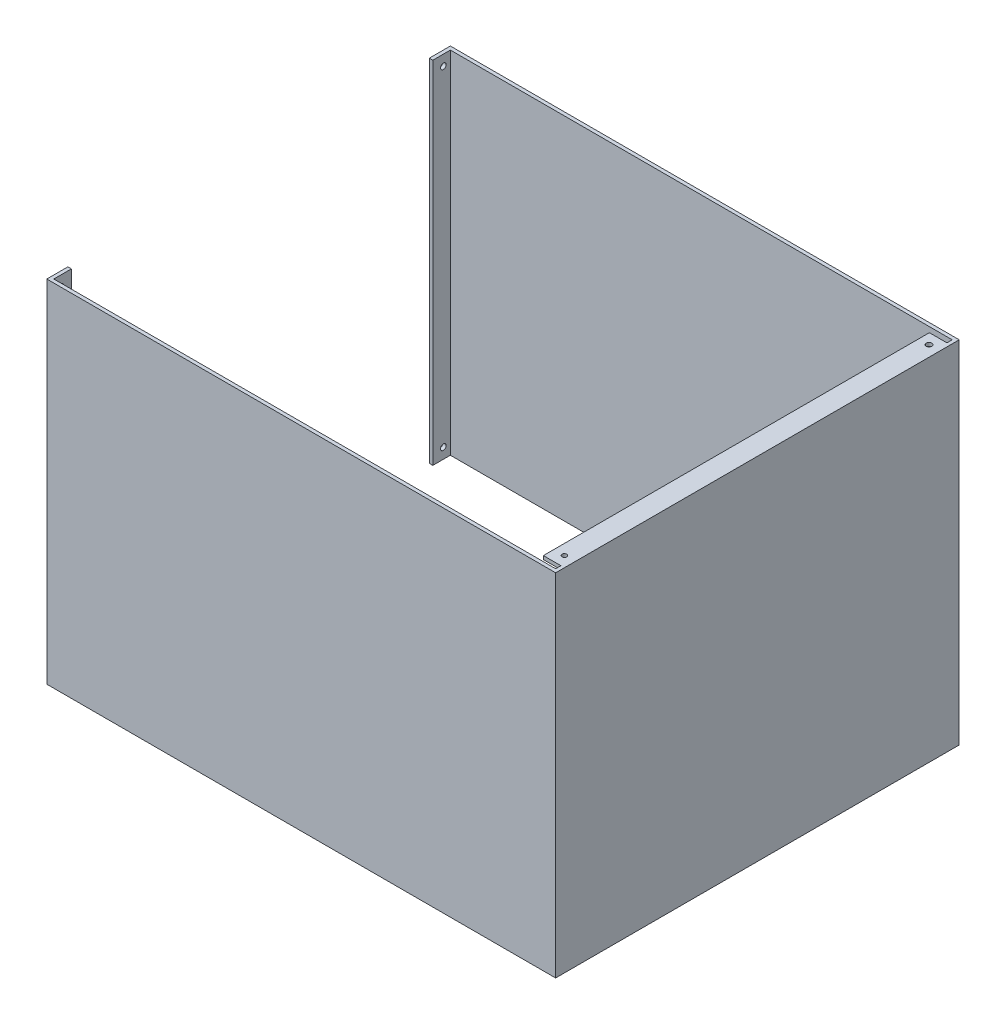
SolidWorks part; units mm, degrees
ref_plane "前视基准面" through (0, 0, 0) normal (0, 0, 1) x (1, 0, 0)
ref_plane "上视基准面" through (0, 0, 0) normal (0, 1, 0) x (1, 0, 0)
ref_plane "右视基准面" through (0, 0, 0) normal (1, 0, 0) x (0, 0, -1)
sketch "草图1" plane through (0, 0, 0) normal (0, 1, 0) x (1, 0, 0)
  line L1 (-145, 115) -> (145, 115)
  line L2 (-145, 115) -> (-145, -115)
  line L3 (-145, -115) -> (145, -115)
  line L4 (145, 115) -> (145, -115)
  line L5 (-145, 115) -> (145, -115) construction
  line L6 (-145, -115) -> (145, 115) construction
  point P0 (0, 0)
  dimension "D1" = 290
  dimension "D2" = 230
extrude "凸台-拉伸1" add sketch "草图1" along normal blind 200
sketch "草图2" plane through (0, 200, 0) normal (0, 1, 0) x (1, 0, 0)
  line L1 (-143, 113) -> (143, 113)
  line L2 (-143, 113) -> (-143, -113)
  line L3 (-143, -113) -> (143, -113)
  line L4 (143, 113) -> (143, -113)
  line L5 (-143, 113) -> (143, -113) construction
  line L6 (-143, -113) -> (143, 113) construction
  point P0 (0, 0)
  dimension "D1" = 286
  dimension "D2" = 226
extrude "切除-拉伸1" cut sketch "草图2" against normal blind 200
sketch "草图3" plane through (-145, 0, 0) normal (-1, 0, 0) x (0, 0, 1)
  line L0 (-115, 200) -> (115, 200) construction
  line L1 (-113, 200) -> (113, 200)
  line L2 (-113, 200) -> (-113, 0)
  line L3 (-113, 0) -> (113, 0)
  line L4 (113, 200) -> (113, 0)
  line L5 (-115, 0) -> (115, 0) construction
  line L6 (115, 200) -> (115, 0) construction
  line L7 (-115, 200) -> (-115, 0) construction
  dimension "D1" = 2
  dimension "D2" = 2
extrude "切除-拉伸2" cut sketch "草图3" against normal blind 2 contours L4 L3 L2 L1
sketch "草图5" plane through (0, 200, 0) normal (0, 1, 0) x (1, 0, 0)
  line L0 (143, -113) -> (143, 113) construction
  line L1 (143, 110) -> (133, 110)
  line L2 (143, 110) -> (143, -110)
  line L3 (143, -110) -> (133, -110)
  line L4 (133, 110) -> (133, -110)
  line L5 (143, 113) -> (-145, 113) construction
  dimension "D1" = 10
  dimension "D2" = 220
  dimension "D3" = 3
extrude "凸台-拉伸2" add sketch "草图5" against normal blind 2
sketch "草图6" plane through (0, 200, 0) normal (0, 1, 0) x (1, 0, 0)
  line L0 (145, -115) -> (145, 115) construction
  line L1 (143, 110) -> (133, 110) construction
  circle A0 centre (138.8254, 104) radius 1.6
  dimension "D1" = 3.2
  dimension "D2" = 6.1746
  dimension "D3" = 6
extrude "切除-拉伸3" cut sketch "草图6" against normal blind 2
sketch "草图7" plane through (0, 200, 0) normal (0, 1, 0) x (1, 0, 0)
  line L0 (145, -115) -> (145, 115) construction
  line L1 (133, -110) -> (143, -110) construction
  circle A0 centre (139, -104) radius 1.3505
  dimension "D1" = 2.7011
  dimension "D2" = 6
  dimension "D3" = 6
extrude "切除-拉伸4" cut sketch "草图7" against normal blind 2
sketch "草图8" plane through (-145, 0, 0) normal (-1, 0, 0) x (0, 0, 1)
  line L0 (113, 0) -> (113, 200) construction
  line L1 (113, 200) -> (103, 200)
  line L2 (113, 200) -> (113, 0)
  line L3 (113, 0) -> (103, 0)
  line L4 (103, 200) -> (103, 0)
  line L5 (113, 200) -> (110, 200) construction
  dimension "D1" = 10
  dimension "D2" = 200
  dimension "D3" = 0
extrude "凸台-拉伸3" add sketch "草图8" against normal blind 2
sketch "草图9" plane through (-145, 0, 0) normal (-1, 0, 0) x (0, 0, 1)
  line L0 (115, 200) -> (115, 0) construction
  line L1 (103, 200) -> (115, 200) construction
  circle A0 centre (109, 194) radius 1.6
  dimension "D1" = 3.2
  dimension "D2" = 6
  dimension "D3" = 6
extrude "切除-拉伸5" cut sketch "草图9" against normal blind 2 contours A0
sketch "草图10" plane through (-145, 0, 0) normal (-1, 0, 0) x (0, 0, 1)
  line L0 (115, 200) -> (115, 0) construction
  line L1 (103, 0) -> (115, 0) construction
  circle A0 centre (109, 6) radius 1.6
  dimension "D1" = 3.2
  dimension "D2" = 6
  dimension "D3" = 6
extrude "切除-拉伸6" cut sketch "草图10" against normal blind 2 contours A0
sketch "草图11" plane through (-145, 0, 0) normal (-1, 0, 0) x (0, 0, 1)
  line L0 (-113, 0) -> (-113, 200) construction
  line L1 (-113, 200) -> (-103, 200)
  line L2 (-113, 200) -> (-113, 0)
  line L3 (-113, 0) -> (-103, 0)
  line L4 (-103, 200) -> (-103, 0)
  line L5 (-110, 200) -> (-113, 200) construction
  dimension "D1" = 10
  dimension "D2" = 200
  dimension "D3" = 0
extrude "凸台-拉伸4" add sketch "草图11" against normal blind 2
sketch "草图12" plane through (-145, 0, 0) normal (-1, 0, 0) x (0, 0, 1)
  line L0 (-115, 200) -> (-115, 0) construction
  line L1 (-115, 200) -> (-103, 200) construction
  circle A0 centre (-109, 194) radius 1.6
  dimension "D1" = 3.2
  dimension "D2" = 6
  dimension "D3" = 6
extrude "切除-拉伸7" cut sketch "草图12" against normal blind 2 contours A0
sketch "草图13" plane through (-145, 0, 0) normal (-1, 0, 0) x (0, 0, 1)
  line L0 (-103, 0) -> (-103, 200) construction
  line L1 (-115, 0) -> (-103, 0) construction
  circle A0 centre (-109, 6) radius 1.6
  dimension "D1" = 3.2
  dimension "D2" = 6
  dimension "D3" = 6
extrude "切除-拉伸8" cut sketch "草图13" against normal blind 2
